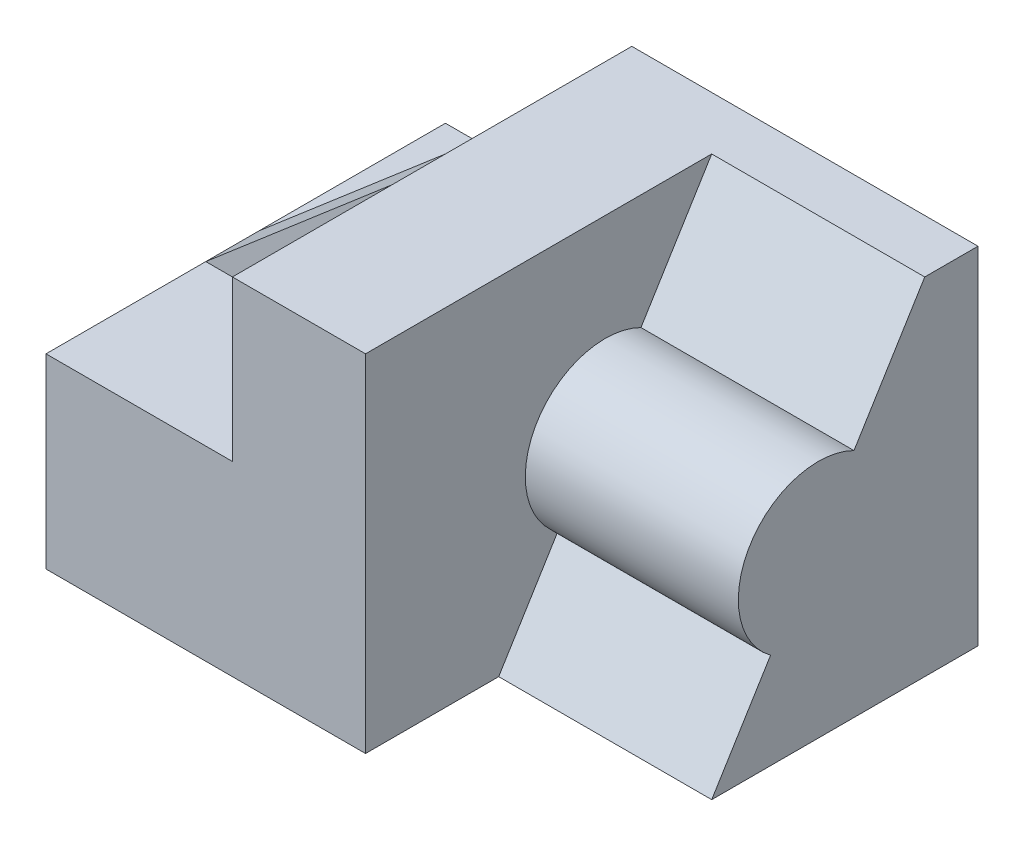
SolidWorks part; units mm, degrees
ref_plane "Plano frontal" through (0, 0, 0) normal (0, 0, 1) x (1, 0, 0)
ref_plane "Plano superior" through (0, 0, 0) normal (0, 1, 0) x (1, 0, 0)
ref_plane "Plano direito" through (0, 0, 0) normal (1, 0, 0) x (0, 0, -1)
sketch "Esboço2" plane through (0, 0, 0) normal (0, 0, 1) x (1, 0, 0)
  line L0 (-60, 35) -> (-60, 0)
  line L1 (-60, 0) -> (0, 0)
  line L2 (0, 0) -> (0, 65)
  line L3 (0, 65) -> (-25, 65)
  line L4 (-25, 65) -> (-25, 35)
  line L5 (-25, 35) -> (-60, 35)
  point P4 (0, 0)
  dimension "D1" = 35
  dimension "D2" = 60
  dimension "D3" = 35
  dimension "D4" = 65
extrude "Ressalto-extrusão1" add sketch "Esboço2" against normal blind 75
sketch "Esboço3" plane through (0, 0, 0) normal (1, 0, 0) x (0, 0, -1)
  line L0 (65, 65) -> (51.7155, 43.4127)
  line L1 (75, 65) -> (0, 65) construction
  line L2 (75, 0) -> (0, 0) construction
  line L3 (36.0527, 17.9606) -> (25, 0)
  line L4 (65, 65) -> (75, 65)
  line L5 (75, 65) -> (75, 0)
  line L6 (75, 0) -> (25, 0)
  arc A0 (51.7155, 43.4127) -> (36.0527, 17.9606) centre (45, 30) ccw
  dimension "D3" = 30
  dimension "D1" = 10
  dimension "D2" = 25
  dimension "D4" = 20
  dimension "D5" = 30
extrude "Ressalto-extrusão2" add sketch "Esboço3" along normal blind 40
sketch "Esboço4" plane through (-25, 0, 0) normal (-1, 0, 0) x (0, 0, 1)
  line L0 (-40, 35) -> (-30, 35)
  line L1 (-75, 35) -> (0, 35) construction
  line L2 (-30, 35) -> (-30, 65)
  line L3 (-75, 65) -> (0, 65) construction
  line L4 (-30, 65) -> (-40, 65)
  line L5 (-40, 65) -> (-40, 35)
  line L6 (0, 65) -> (0, 35) construction
  dimension "D1" = 10
  dimension "D2" = 30
extrude "Ressalto-extrusão3" add sketch "Esboço4" along normal blind 35
sketch "Esboço6" plane through (0, 0, -30) normal (0, 0, 1) x (1, 0, 0)
  line L0 (-25, 65) -> (-60, 35)
  line L1 (-25, 65) -> (-60, 65)
  line L2 (-60, 65) -> (-60, 35)
extrude "Corte-extrusão1" cut sketch "Esboço6" against normal up to next
